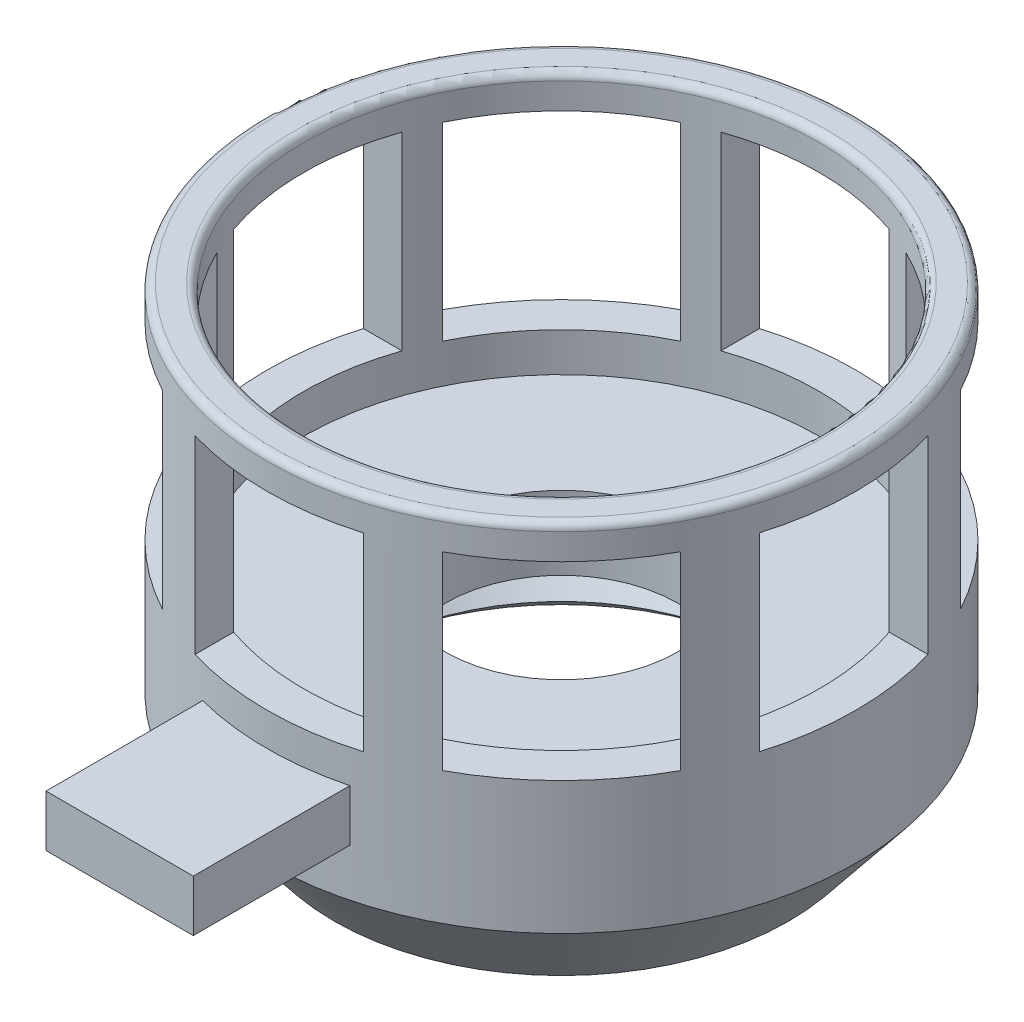
SolidWorks part; units mm, degrees
material "PBT 一般用途"
ref_plane "前视基准面" through (0, 0, 0) normal (0, 0, 1) x (1, 0, 0)
ref_plane "上视基准面" through (0, 0, 0) normal (0, 1, 0) x (1, 0, 0)
ref_plane "右视基准面" through (0, 0, 0) normal (1, 0, 0) x (0, 0, -1)
sketch "草图1" plane through (0, 0, 0) normal (0, 0, 1) x (1, 0, 0)
  line L0 (-1000, 0.1826) -> (-35, 0.1826) construction
  line L1 (0, 0) -> (0, 5.3837) construction
  line L25 (-15, 0.1826) -> (0, 0.1826) construction
  line L27 (-35.7649, -13.5696) -> (-26.9534, -24.5602)
  line L28 (-15.7649, -3.5696) -> (-35, -3.5696)
  line L30 (-15.7649, -13.5696) -> (-35.7649, -13.5696)
  line L32 (-39, 31.9776) -> (-36, 31.9776)
  line L33 (-40, 30.9776) -> (-40, -16.2805)
  line L35 (-35, 30.9776) -> (-35, -3.5696)
  line L36 (-26.9534, -24.5602) -> (-30.8545, -27.6878)
  line L37 (-30.8545, -27.6878) -> (-40, -16.2805)
  line L38 (-15.7649, -13.5696) -> (-15.7649, -3.5696)
  arc A0 (-36, 31.9776) -> (-35, 30.9776) centre (-36, 30.9776) cw
  arc A1 (-39, 31.9776) -> (-40, 30.9776) centre (-39, 30.9776) ccw
  point P4 (0, 0)
  point P10 (-35, 31.9776)
  point P22 (-40, 31.9776)
  dimension "D4" = 5
  dimension "D5" = 1
  dimension "D1" = 20
  dimension "D2" = 10
  dimension "D3" = 5
revolve "旋转4" add sketch "草图1" angle 360 about L1
ref_plane "基准面5" through (0, 0, 40) normal (0, 0, 1) x (1, 0, 0)
sketch "草图9" plane through (0, 0, 40) normal (0, 0, 1) x (1, 0, 0)
  line L0 (0, -200000) -> (0, 200005.3837) construction
  line L1 (-11.4318, 27.4483) -> (11.4318, 27.4483)
  line L2 (-11.4318, 27.4483) -> (-11.4318, 1.7138)
  line L3 (-11.4318, 1.7138) -> (11.4318, 1.7138)
  line L4 (11.4318, 27.4483) -> (11.4318, 1.7138)
  line L5 (-11.4318, 27.4483) -> (11.4318, 1.7138) construction
  line L6 (-11.4318, 1.7138) -> (11.4318, 27.4483) construction
  point P0 (0, 14.581)
extrude "切除-拉伸7" cut sketch "草图9" against normal up to surface (6.9196 mm away)
pattern_circular "阵列(圆周)3" count 8 every 45 about axis through (0, 0, 0) along (0, 1, 0) of "切除-拉伸7"
sketch "草图11" plane through (0, 0, 40) normal (0, 0, 1) x (1, 0, 0)
  line L0 (0, -200000) -> (0, 200005.3837) construction
  line L1 (-10, -2.8015) -> (10, -2.8015)
  line L2 (-10, -2.8015) -> (-10, -9.8015)
  line L3 (-10, -9.8015) -> (10, -9.8015)
  line L4 (10, -2.8015) -> (10, -9.8015)
  line L5 (-10, -2.8015) -> (10, -9.8015) construction
  line L6 (-10, -9.8015) -> (10, -2.8015) construction
  point P0 (0, -6.3015)
  dimension "D1" = 20
  dimension "D2" = 7
extrude "凸台-拉伸1" add sketch "草图11" along normal blind 20 and the other way up to next
